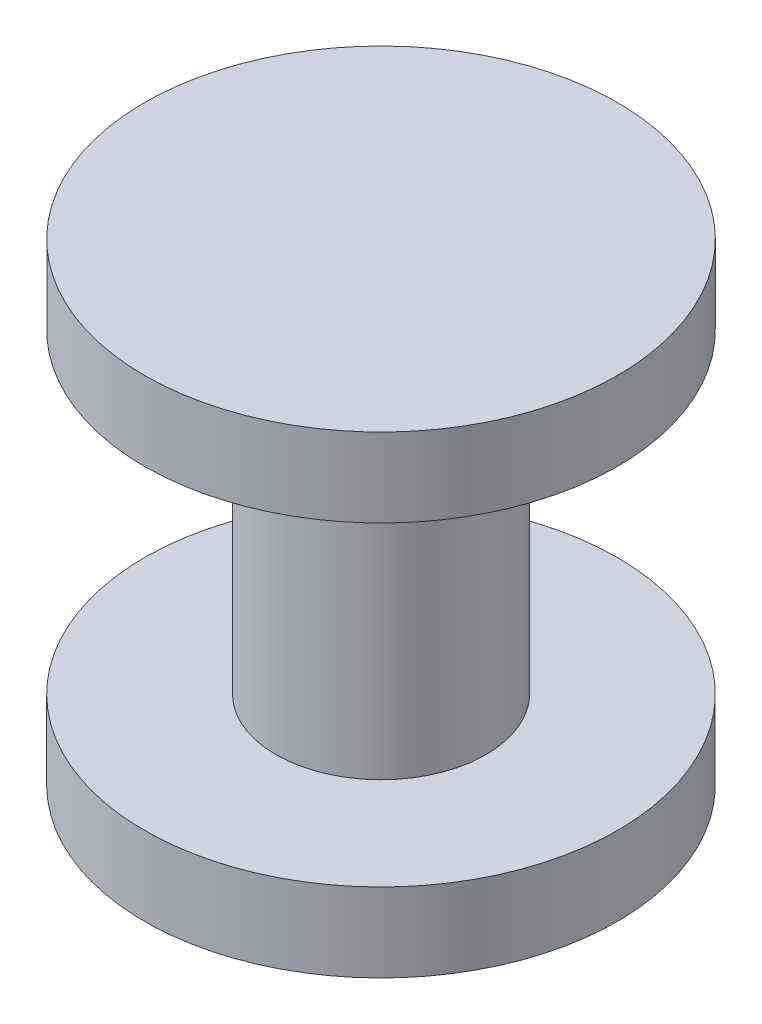
SolidWorks part; units mm, degrees
ref_plane "Front Plane" through (0, 0, 0) normal (0, 0, 1) x (1, 0, 0)
ref_plane "Top Plane" through (0, 0, 0) normal (0, 1, 0) x (1, 0, 0)
ref_plane "Right Plane" through (0, 0, 0) normal (1, 0, 0) x (0, 0, -1)
sketch "Sketch1" plane through (0, 0, 0) normal (0, 1, 0) x (1, 0, 0)
  circle A0 centre (0, 0) radius 2
  dimension "D1" = 4
extrude "Boss-Extrude1" add sketch "Sketch1" along normal blind 6
sketch "Sketch2" plane through (0, 6, 0) normal (0, 1, 0) x (1, 0, 0)
  circle A0 centre (0, 0) radius 4.5
  dimension "D1" = 9
extrude "Boss-Extrude2" add sketch "Sketch2" along normal blind 1.5
sketch "Sketch3" plane through (0, 0, 0) normal (0, -1, 0) x (1, 0, 0)
  circle A0 centre (0, 0) radius 4.5
  dimension "D1" = 9
extrude "Boss-Extrude3" add sketch "Sketch3" along normal blind 1.5
